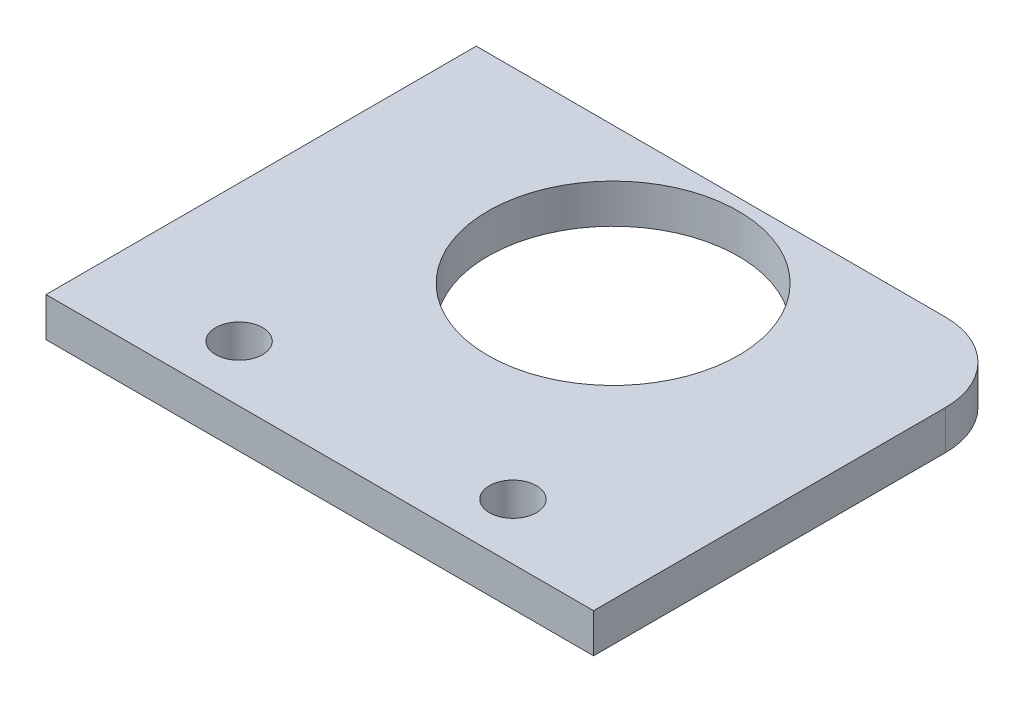
SolidWorks part; units mm, degrees
material "AISI 304"
ref_plane "Plan de face" through (0, 0, 0) normal (0, 0, 1) x (1, 0, 0)
ref_plane "Plan de dessus" through (0, 0, 0) normal (0, 1, 0) x (1, 0, 0)
ref_plane "Plan de droite" through (0, 0, 0) normal (1, 0, 0) x (0, 0, -1)
sketch "Sketch1" plane through (0, 0, 0) normal (0, 1, 0) x (1, 0, 0)
  line L0 (0, 0) -> (0, 10) construction
  line L1 (-35, 27.5) -> (35, 27.5)
  line L2 (-35, 27.5) -> (-35, -27.5)
  line L3 (-35, -27.5) -> (35, -27.5)
  line L4 (35, 27.5) -> (35, -27.5)
  line L5 (-35, 27.5) -> (35, -27.5) construction
  line L6 (-35, -27.5) -> (35, 27.5) construction
  circle A0 centre (0, 10) radius 16
  point P0 (0, 0)
  dimension "D1" = 32
  dimension "D2" = 55
  dimension "D3" = 70
  dimension "D4" = 10
extrude "Boss-Extrude1" add sketch "Sketch1" along normal blind 5
sketch "Sketch2" plane through (0, 5, 0) normal (0, 1, 0) x (1, 0, 0)
  line L0 (0, 10) -> (-17.5, -20.3109) construction
  line L1 (-17.5, -20.3109) -> (17.5, -20.3109) construction
  line L3 (-35, -27.5) -> (35, -27.5) construction
  line L4 (0, 10) -> (0, -20.3109) construction
  circle A0 centre (-17.5, -20.3109) radius 3
  circle A1 centre (17.5, -20.3109) radius 3
  dimension "D3" = 6
  dimension "D4" = 6
  dimension "D1" = 35
  dimension "D2" = 35
extrude "Cut-Extrude1" cut sketch "Sketch2" against normal through all
fillet "Fillet1" radius 10 1 edges at (35, 2.5, -27.5)
